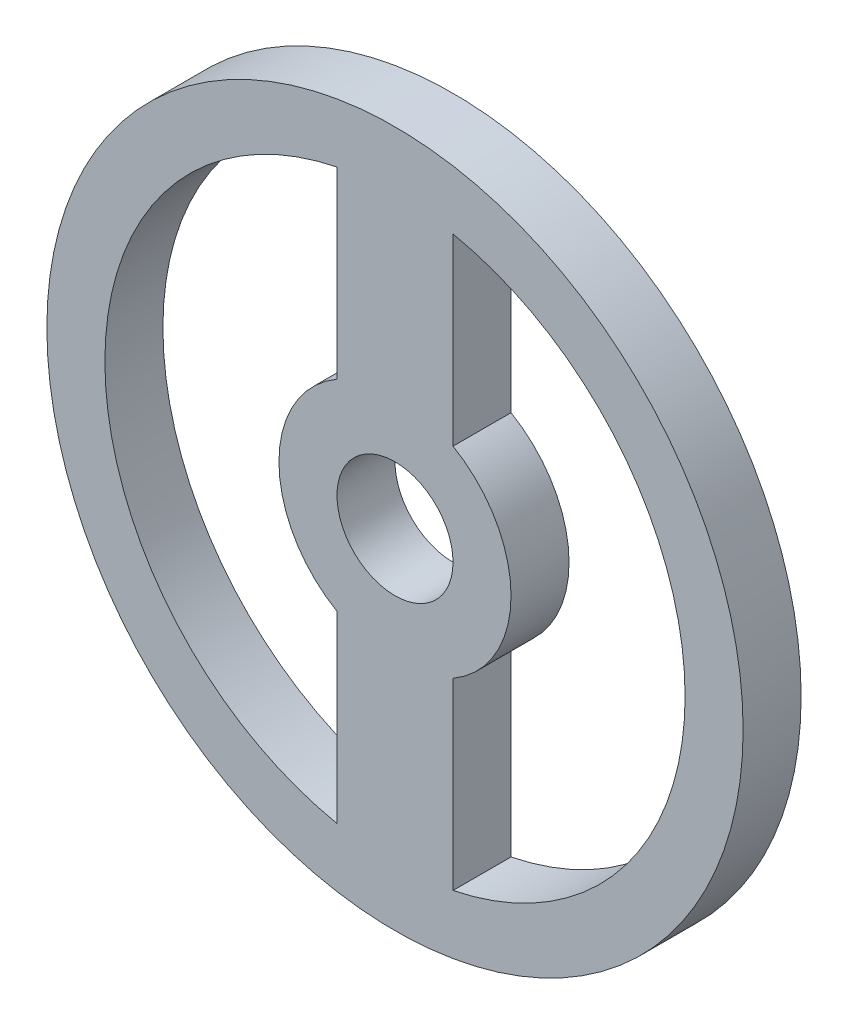
SolidWorks part; units mm, degrees
material "Nickel"
ref_plane "Front" through (0, 0, 0) normal (0, 0, 1) x (1, 0, 0)
ref_plane "Top" through (0, 0, 0) normal (0, 1, 0) x (1, 0, 0)
ref_plane "Right" through (0, 0, 0) normal (1, 0, 0) x (0, 0, -1)
sketch "Sketch1" plane through (0, 0, 0) normal (0, 0, 1) x (1, 0, 0)
  line L2 (-5, 24.4949) -> (-5, 8.6603)
  line L4 (5, 24.4949) -> (5, 8.6603)
  line L5 (-5, -8.6603) -> (-5, -24.4949)
  line L6 (5, -8.6603) -> (5, -24.4949)
  circle A0 centre (0, 0) radius 30
  arc A1 (-5, 24.4949) -> (-5, -24.4949) centre (0, 0) ccw
  arc A2 (-5, 8.6603) -> (-5, -8.6603) centre (0, 0) ccw
  circle A3 centre (0, 0) radius 5
  circle A4 centre (0, 0) radius 25 construction
  arc A5 (5, -24.4949) -> (5, 24.4949) centre (0, 0) ccw
  arc A6 (5, -8.6603) -> (5, 8.6603) centre (0, 0) ccw
  dimension "D1" = 60
  dimension "D2" = 5
extrude "Boss-Extrude1" add sketch "Sketch1" along normal blind 5
